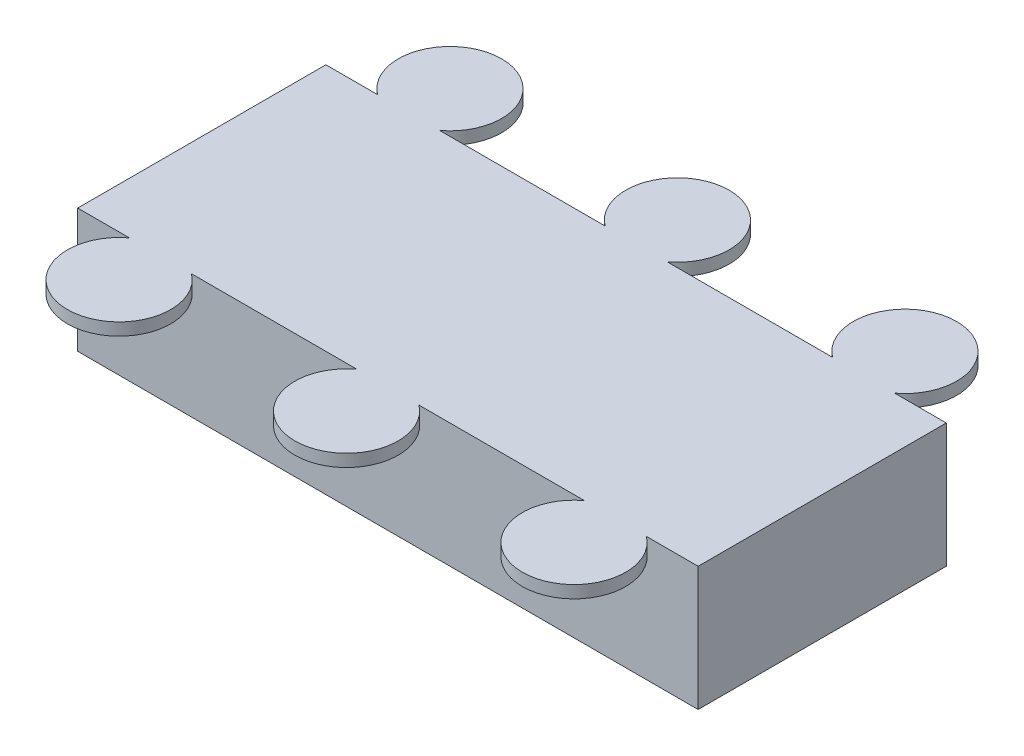
SolidWorks part; units mm, degrees
ref_plane "Front Plane" through (0, 0, 0) normal (0, 0, 1) x (1, 0, 0)
ref_plane "Top Plane" through (0, 0, 0) normal (0, 1, 0) x (1, 0, 0)
ref_plane "Right Plane" through (0, 0, 0) normal (1, 0, 0) x (0, 0, -1)
sketch "Sketch1" plane through (0, 0, 0) normal (0, 1, 0) x (1, 0, 0)
  line L0 (-1027.1312, 0) -> (1014.7607, 0) construction
  line L1 (-750, 300) -> (750, 300)
  line L2 (-750, 300) -> (-750, -300)
  line L3 (-750, -300) -> (750, -300)
  line L4 (750, 300) -> (750, -300)
  line L5 (-750, 300) -> (750, -300) construction
  line L6 (-750, -300) -> (750, 300) construction
  line L7 (0, 464.4896) -> (0, -458.0029) construction
  point P0 (0, 0)
  dimension "D1" = 600
  dimension "D2" = 1500
extrude "Boss-Extrude1" add sketch "Sketch1" along normal blind 300
sketch "Sketch2" plane through (0, 300, 0) normal (0, 1, 0) x (1, 0, 0)
  line L0 (0, -429.7246) -> (0, 351.9715) construction
  line L1 (-881.6644, 0) -> (820.5727, 0) construction
  line L2 (-75, -300) -> (75, -300)
  line L3 (-750, -300) -> (750, -300) construction
  line L4 (-75, 300) -> (75, 300)
  line L5 (-550, 400) -> (-550, -429.7246) construction
  line L7 (550, -429.7246) -> (550, 400) construction
  line L9 (-275, 400) -> (-275, -429.7246) construction
  line L10 (625, -300) -> (475, -300)
  line L11 (275, -429.7246) -> (275, 400) construction
  line L12 (625, 300) -> (475, 300)
  line L13 (-475, -300) -> (-625, -300)
  line L14 (-475, 300) -> (-625, 300)
  arc A0 (-75, -300) -> (75, -300) centre (0, -400) ccw
  arc A1 (-75, 300) -> (75, 300) centre (0, 400) cw
  arc A2 (625, -300) -> (475, -300) centre (550, -400) cw
  arc A3 (625, 300) -> (475, 300) centre (550, 400) ccw
  arc A4 (-475, -300) -> (-625, -300) centre (-550, -400) cw
  arc A5 (-475, 300) -> (-625, 300) centre (-550, 400) ccw
  dimension "D1" = 250
  dimension "D2" = 400
  dimension "D5" = 275
  dimension "D6" = 275
extrude "Boss-Extrude2" add sketch "Sketch2" against normal blind 30
